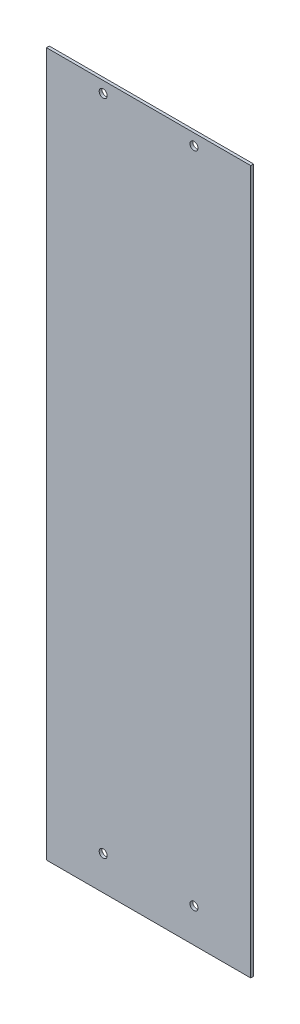
SolidWorks part; units mm, degrees
material "ABS PC"
ref_plane "Front Plane" through (0, 0, 0) normal (0, 0, 1) x (1, 0, 0)
ref_plane "Top Plane" through (0, 0, 0) normal (0, 1, 0) x (1, 0, 0)
ref_plane "Right Plane" through (0, 0, 0) normal (1, 0, 0) x (0, 0, -1)
sketch "Sketch1" plane through (0, 0, 0) normal (0, 0, 1) x (1, 0, 0)
  line L0 (57.15, 0) -> (57.15, 36.4707) construction
  line L1 (0, 0) -> (114.3, 0)
  line L2 (0, 0) -> (0, 393.7)
  line L3 (0, 393.7) -> (114.3, 393.7)
  line L4 (114.3, 0) -> (114.3, 393.7)
  circle A0 centre (31.75, 387.35) radius 2.25
  circle A1 centre (82.55, 387.35) radius 2.25
  circle A2 centre (31.75, 19.05) radius 2.25
  circle A3 centre (82.55, 19.05) radius 2.25
  dimension "D5" = 4.5
  dimension "D1" = 114.3
  dimension "D2" = 368.3
  dimension "D3" = 57.15
  dimension "D4" = 6.35
  dimension "D6" = 25.4
  dimension "D7" = 25.4
  dimension "D8" = 19.05
extrude "Boss-Extrude1" add sketch "Sketch1" along normal blind 1.5875
